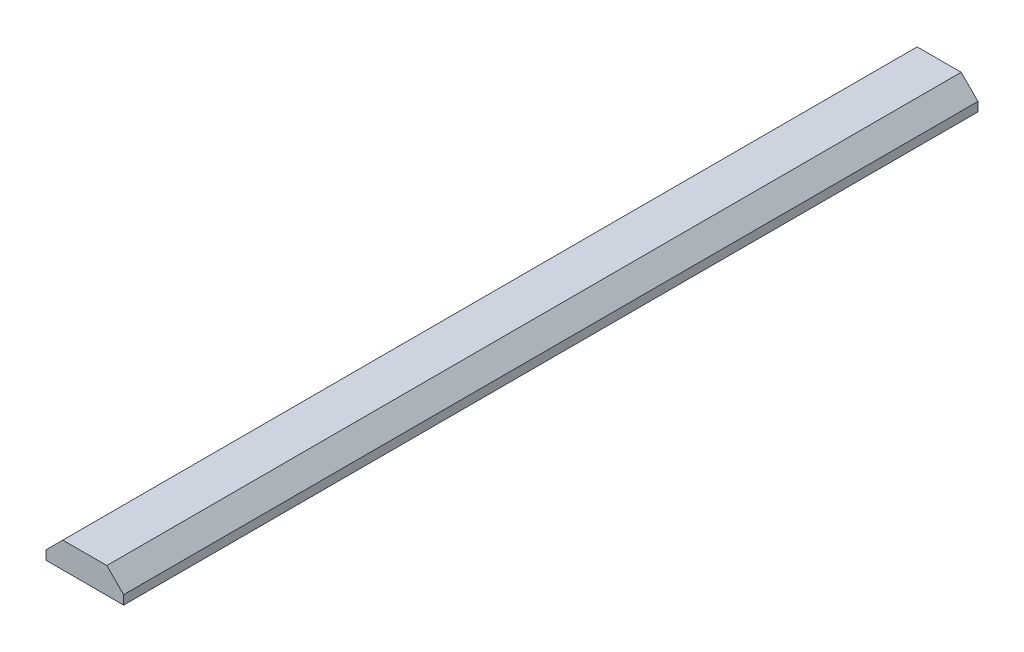
SolidWorks part; units mm, degrees
ref_plane "Ebene vorne" through (0, 0, 0) normal (0, 0, 1) x (1, 0, 0)
ref_plane "Ebene oben" through (0, 0, 0) normal (0, 1, 0) x (1, 0, 0)
ref_plane "Ebene rechts" through (0, 0, 0) normal (1, 0, 0) x (0, 0, -1)
sketch "Skizze1" plane through (0, 0, 0) normal (0, 0, 1) x (1, 0, 0)
  line L0 (0, 0) -> (0, 23680.6173) construction
  line L1 (3.4, 1.8089) -> (-3.4, 1.8089)
  line L2 (-3.4, 1.8089) -> (-6, -0.7911)
  line L3 (-6, -0.7911) -> (-6, -2.1911)
  line L4 (-6, -2.1911) -> (6, -2.1911)
  line L5 (6, -0.7911) -> (6, -2.1911)
  line L6 (3.4, 1.8089) -> (6, -0.7911)
  point P9 (0, -2.1911)
  point P11 (0, 1.8089)
  dimension "D1" = 3.4
  dimension "D2" = 6
  dimension "D3" = 4
  dimension "D4" = 135
extrude "Aufsatz-Linear austragen1" add sketch "Skizze1" along normal blind 132 contours L1 L2 L3 L4 L5 L6
